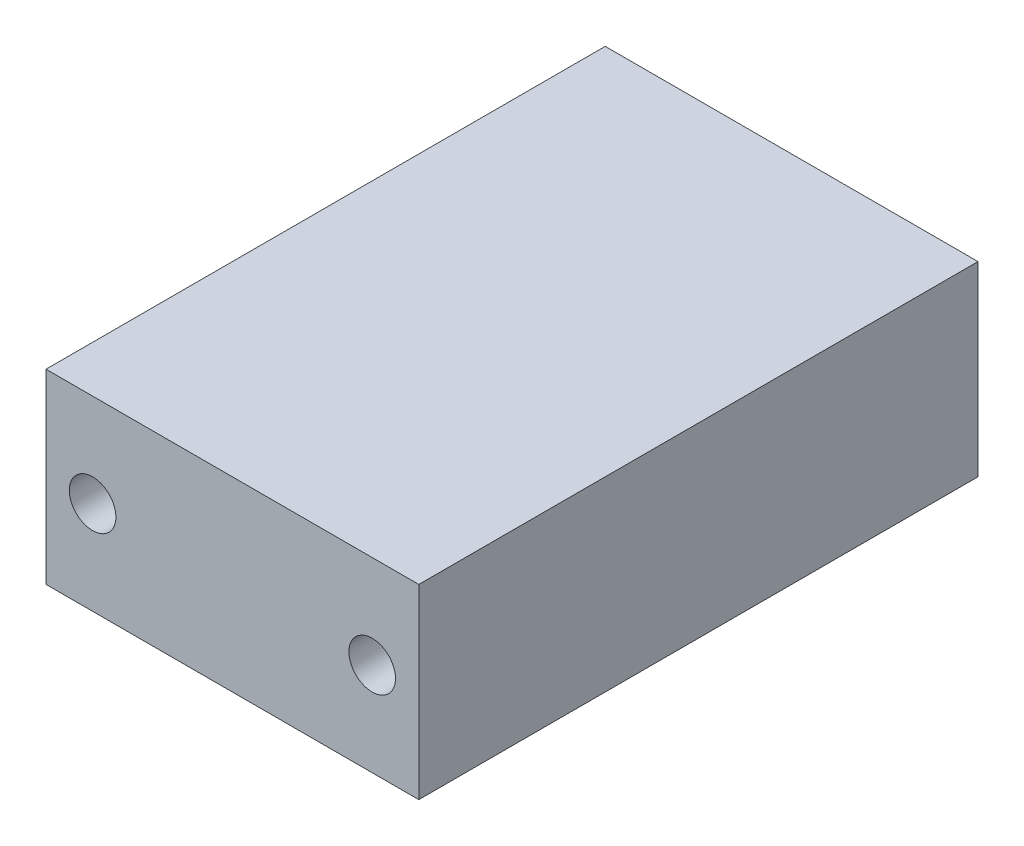
SolidWorks part; units mm, degrees
material "1060 合金"
ref_plane "前视基准面" through (0, 0, 0) normal (0, 0, 1) x (1, 0, 0)
ref_plane "上视基准面" through (0, 0, 0) normal (0, 1, 0) x (1, 0, 0)
ref_plane "右视基准面" through (0, 0, 0) normal (1, 0, 0) x (0, 0, -1)
sketch "草图1" plane through (0, 0, 0) normal (0, 0, 1) x (1, 0, 0)
  line L1 (-40, 20) -> (40, 20)
  line L2 (-40, 20) -> (-40, -20)
  line L3 (-40, -20) -> (40, -20)
  line L4 (40, 20) -> (40, -20)
  line L5 (-40, 20) -> (40, -20) construction
  line L6 (-40, -20) -> (40, 20) construction
  point P0 (0, 0)
  dimension "D1" = 80
  dimension "D2" = 40
extrude "凸台-拉伸1" add sketch "草图1" along normal blind 120
sketch "草图2" plane through (0, 0, 120) normal (0, 0, 1) x (1, 0, 0)
  line L0 (-30, 0) -> (30, 0) construction
  circle A0 centre (-30, 0) radius 5
  circle A1 centre (30, 0) radius 5
  point P4 (0, 0)
  dimension "D2" = 10
  dimension "D3" = 10
  dimension "D1" = 60
extrude "切除-拉伸1" cut sketch "草图2" against normal blind 120
